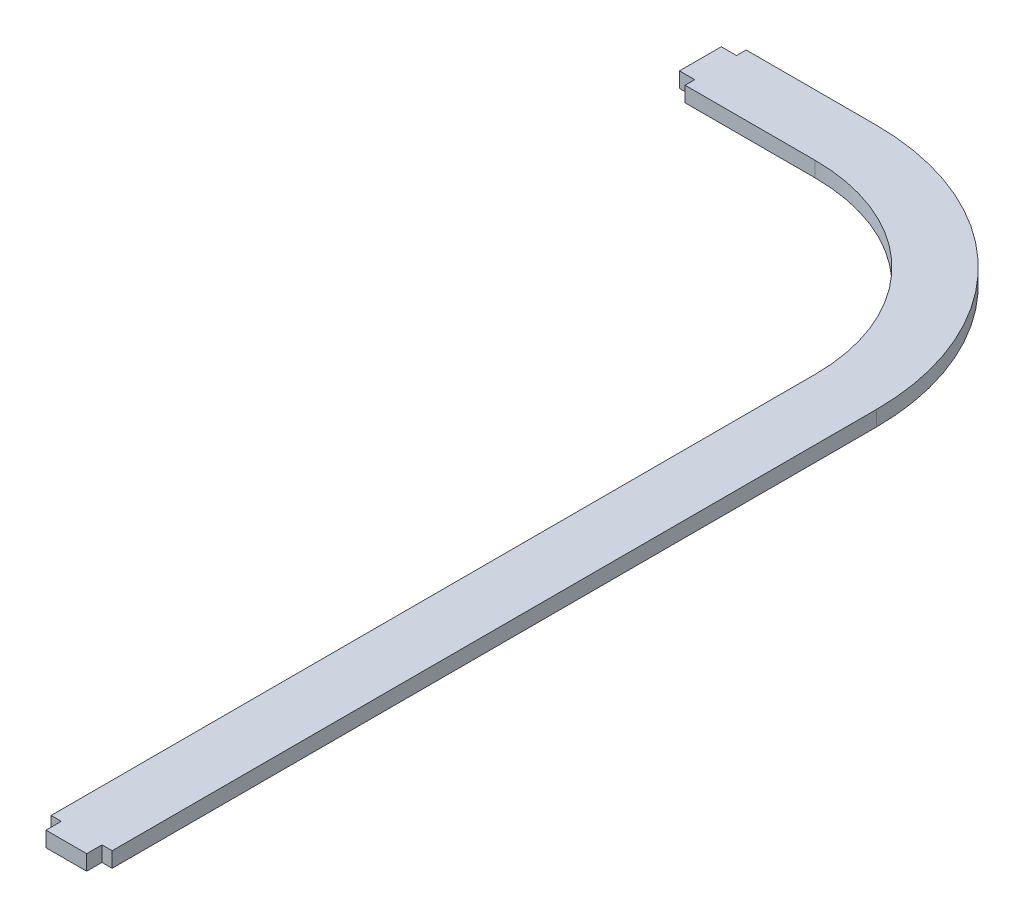
SolidWorks part; units mm, degrees
ref_plane "Alzado" through (0, 0, 0) normal (0, 0, 1) x (1, 0, 0)
ref_plane "Planta" through (0, 0, 0) normal (0, 1, 0) x (1, 0, 0)
ref_plane "Vista lateral" through (0, 0, 0) normal (1, 0, 0) x (0, 0, -1)
sketch "Croquis1" plane through (0, 0, 0) normal (0, 1, 0) x (1, 0, 0)
  line L0 (0, 0) -> (0, 8)
  line L1 (0, 8) -> (3, 8)
  line L2 (3, -2.107) -> (3, -0.2139)
  line L3 (3, 9.893) -> (28.5736, 9.893)
  line L5 (72.5, 3.893) -> (72.5, -188.737) construction
  line L6 (3, -2.107) -> (7.3583, -2.107)
  line L7 (0, -0.2139) -> (3, -0.2139)
  line L8 (0, 7.7861) -> (0, -0.2139)
  line L9 (3, 8) -> (3, 9.893)
  line L10 (65, -188.737) -> (67, -188.737)
  line L11 (77, -188.737) -> (77, -38.5334)
  line L12 (75, -191.737) -> (67, -191.737)
  line L13 (67, -191.737) -> (67, -188.737)
  line L14 (7.3583, -2.107) -> (28.5736, -2.107)
  line L15 (75, -191.737) -> (75, -188.737)
  line L16 (75, -188.737) -> (77, -188.737)
  line L17 (65, -117.737) -> (65, -188.737)
  line L19 (71, 3.893) -> (28.5736, -38.5334) construction
  line L20 (65, -117.737) -> (65, -38.5334)
  line L21 (71, -105.737) -> (71, 3.893) construction
  line L22 (77, -188.737) -> (77, -38.5334)
  line L23 (3, -2.107) -> (3, -191.737) construction
  arc A1 (65, -38.5334) -> (28.5736, -2.107) centre (28.5736, -38.5334) ccw
  arc A2 (77, -38.5334) -> (28.5736, 9.893) centre (28.5736, -38.5334) ccw
  dimension "D1" = 8
  dimension "D2" = 3
  dimension "D5" = 192.63
  dimension "D12" = 60
extrude "Saliente-Extruir1" add sketch "Croquis1" along normal blind 3
